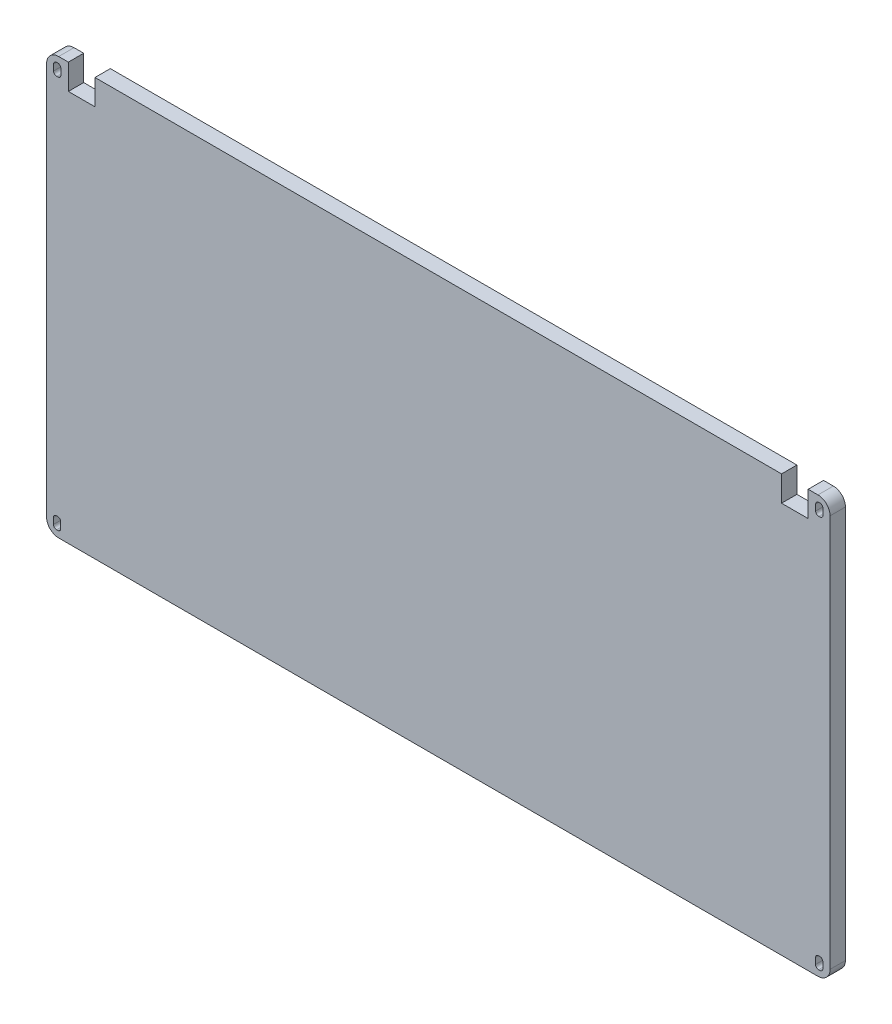
SolidWorks part; units mm, degrees
ref_plane "Front Plane" through (0, 0, 0) normal (0, 0, 1) x (1, 0, 0)
ref_plane "Top Plane" through (0, 0, 0) normal (0, 1, 0) x (1, 0, 0)
ref_plane "Right Plane" through (0, 0, 0) normal (1, 0, 0) x (0, 0, -1)
sketch "Sketch1" plane through (0, 0, 0) normal (0, 0, 1) x (1, 0, 0)
  line L0 (307.6251, 169.7001) -> (325.7251, 169.7001)
  line L1 (-321.9749, 169.7001) -> (-303.9749, 169.7001)
  line L2 (-321.9749, 169.7001) -> (-321.9749, -174.9779)
  line L3 (-321.9749, -174.9779) -> (325.7251, -174.9779)
  line L4 (325.7251, 169.7001) -> (325.7251, -174.9779)
  line L6 (-303.9749, 169.7001) -> (-303.9749, 148.7001)
  line L7 (-303.9749, 148.7001) -> (-281.9749, 148.7001)
  line L8 (-281.9749, 169.7001) -> (-281.9749, 148.7001)
  line L10 (285.6251, 169.7001) -> (285.6251, 148.7001)
  line L11 (285.6251, 148.7001) -> (307.6251, 148.7001)
  line L12 (307.6251, 169.7001) -> (307.6251, 148.7001)
  line L13 (317.2216, -169.9779) -> (316.2216, -169.9779)
  line L14 (319.7216, -167.4779) -> (319.7216, -162.4779)
  line L15 (317.2216, -159.9779) -> (316.2216, -159.9779)
  line L16 (313.7216, -167.4779) -> (313.7216, -162.4779)
  line L17 (-312.7784, -169.9779) -> (-313.7784, -169.9779)
  line L18 (-316.2784, -167.4779) -> (-316.2784, -162.4779)
  line L19 (-312.7784, -159.9779) -> (-313.7784, -159.9779)
  line L20 (-310.2784, -167.4779) -> (-310.2784, -162.4779)
  line L21 (-312.6749, 154.7021) -> (-313.6749, 154.7021)
  line L22 (-316.1749, 157.2021) -> (-316.1749, 162.2021)
  line L23 (-312.6749, 164.7021) -> (-313.6749, 164.7021)
  line L24 (-310.1749, 157.2021) -> (-310.1749, 162.2021)
  line L25 (317.3251, 154.7021) -> (316.3251, 154.7021)
  line L26 (313.8251, 157.2021) -> (313.8251, 162.2021)
  line L27 (317.3251, 164.7021) -> (316.3251, 164.7021)
  line L28 (319.8251, 157.2021) -> (319.8251, 162.2021)
  line L29 (-281.9749, 169.7001) -> (285.6251, 169.7001)
  line L32 (319.8251, 719.4221) -> (319.8251, -174.9779) construction
  line L33 (319.7216, 719.4221) -> (319.7216, -174.9779) construction
  arc A0 (317.2216, -169.9779) -> (319.7216, -167.4779) centre (317.2216, -167.4779) ccw
  arc A1 (319.7216, -162.4779) -> (317.2216, -159.9779) centre (317.2216, -162.4779) ccw
  arc A2 (316.2216, -169.9779) -> (313.7216, -167.4779) centre (316.2216, -167.4779) cw
  arc A3 (316.2216, -159.9779) -> (313.7216, -162.4779) centre (316.2216, -162.4779) ccw
  arc A4 (-313.7784, -169.9779) -> (-316.2784, -167.4779) centre (-313.7784, -167.4779) cw
  arc A5 (-313.7784, -159.9779) -> (-316.2784, -162.4779) centre (-313.7784, -162.4779) ccw
  arc A6 (-310.2784, -162.4779) -> (-312.7784, -159.9779) centre (-312.7784, -162.4779) ccw
  arc A7 (-312.7784, -169.9779) -> (-310.2784, -167.4779) centre (-312.7784, -167.4779) ccw
  arc A8 (-313.6749, 154.7021) -> (-316.1749, 157.2021) centre (-313.6749, 157.2021) cw
  arc A9 (-313.6749, 164.7021) -> (-316.1749, 162.2021) centre (-313.6749, 162.2021) ccw
  arc A10 (-310.1749, 162.2021) -> (-312.6749, 164.7021) centre (-312.6749, 162.2021) ccw
  arc A11 (-312.6749, 154.7021) -> (-310.1749, 157.2021) centre (-312.6749, 157.2021) ccw
  arc A12 (316.3251, 154.7021) -> (313.8251, 157.2021) centre (316.3251, 157.2021) cw
  arc A13 (316.3251, 164.7021) -> (313.8251, 162.2021) centre (316.3251, 162.2021) ccw
  arc A14 (319.8251, 162.2021) -> (317.3251, 164.7021) centre (317.3251, 162.2021) ccw
  arc A15 (317.3251, 154.7021) -> (319.8251, 157.2021) centre (317.3251, 157.2021) ccw
  point P12 (307.6251, 159.2001)
  point P26 (316.7216, -169.9779)
  point P27 (316.6751, 169.7001)
  dimension "D11" = 2.5
  dimension "D1" = 647.7
  dimension "D2" = 344.678
  dimension "D3" = 21
  dimension "D4" = 22
  dimension "D5" = 21
  dimension "D6" = 22
  dimension "D7" = 18.1
  dimension "D8" = 18
  dimension "D9" = 169.7001
  dimension "D10" = 321.9749
  dimension "D12" = 6
  dimension "D13" = 10
  dimension "5" = 5
  dimension "D17" = 4.998
  dimension "D18" = 5.8
  dimension "D14" = 2
  dimension "D15" = 2
extrude "Boss-Extrude1" add sketch "Sketch1" along normal blind 12.7 contours L4 L3 L2 L1 L6 L7 L8 L29 L10 L11 L12 L0 | L14 A1 L15 A3 L16 A2 L13 A0 | L20 A6 L19 A5 L18 A4 L17 A7 | L24 A10 L23 A9 L22 A8 L21 A11 | L28 A14 L27 A13 L26 A12 L25 A15
fillet "Fillet1" radius 10 4 edges at (-321.9749, -174.9779, 6.35) (-321.9749, 169.7001, 6.35) (325.7251, -174.9779, 6.35) (325.7251, 169.7001, 6.35)
equation "\"D5@Sketch1\"=\"D3@Sketch1\""
equation "\"D6@Sketch1\"=\"D4@Sketch1\""
